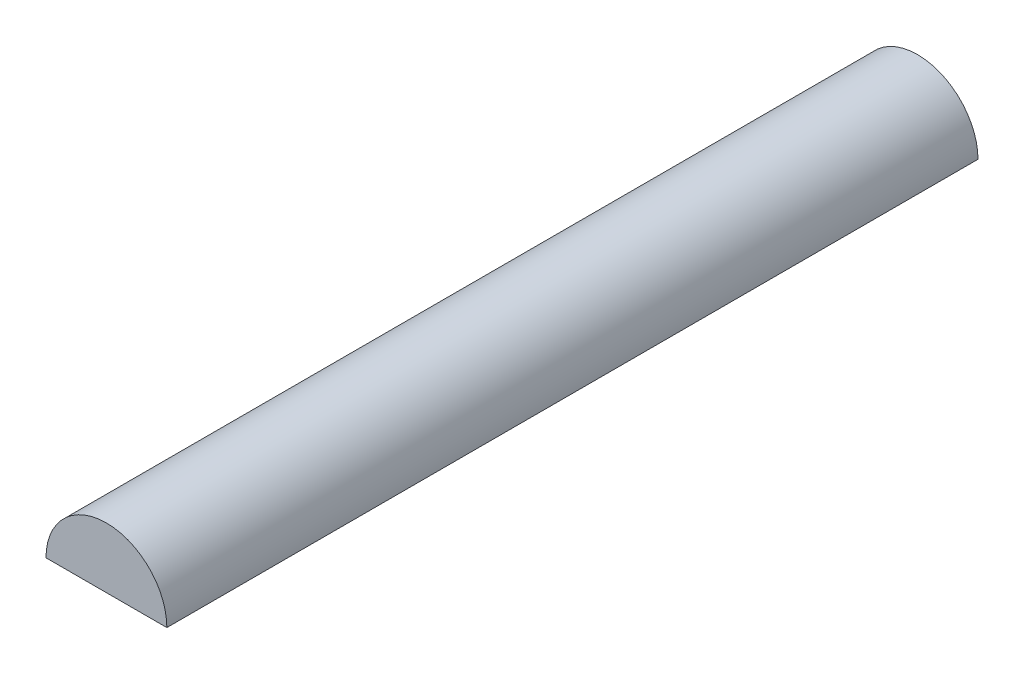
SolidWorks part; units mm, degrees
ref_plane "Front" through (0, 0, 0) normal (0, 0, 1) x (1, 0, 0)
ref_plane "Top" through (0, 0, 0) normal (0, 1, 0) x (1, 0, 0)
ref_plane "Right" through (0, 0, 0) normal (1, 0, 0) x (0, 0, -1)
other "Configuration Table"
sketch "Sketch1" plane through (0, 0, 0) normal (0, 0, 1) x (1, 0, 0)
  line L0 (-0.745, 0) -> (0.745, 0)
  arc A0 (-0.745, 0) -> (0.745, 0) centre (0, 0) cw
  dimension "D2" = 0.745
  dimension "D1" = 1.49
extrude "Extrude1" add sketch "Sketch1" along normal blind 10
